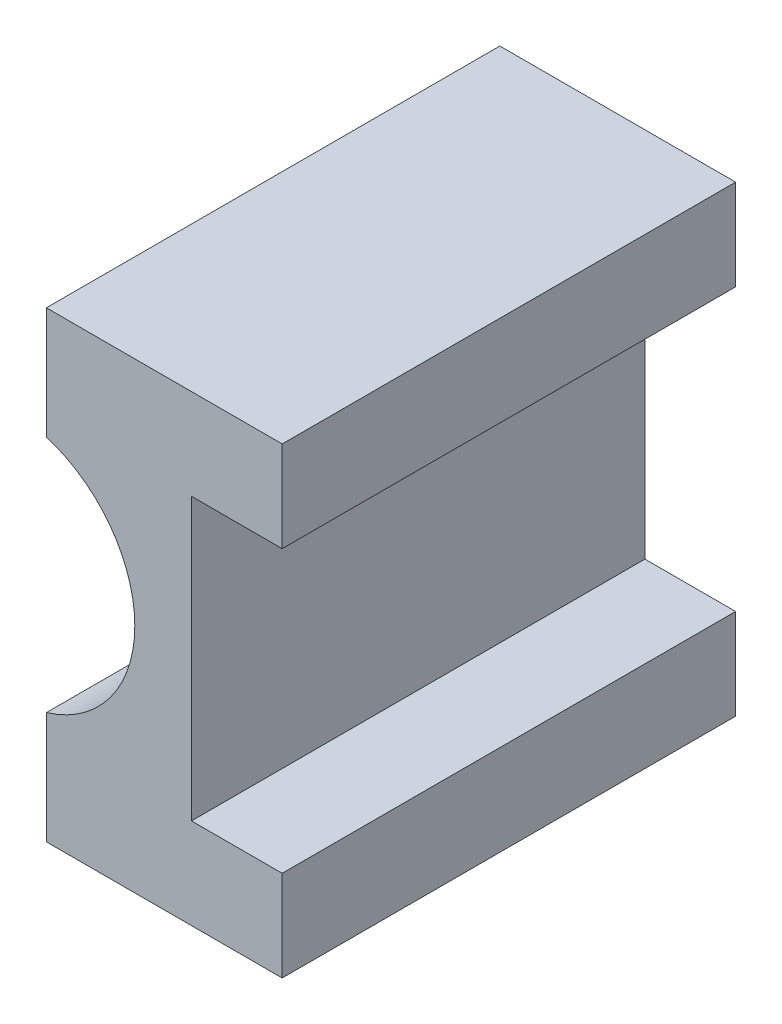
SolidWorks part; units mm, degrees
ref_plane "正面" through (0, 0, 0) normal (0, 0, 1) x (1, 0, 0)
ref_plane "平面" through (0, 0, 0) normal (0, 1, 0) x (1, 0, 0)
ref_plane "右側面" through (0, 0, 0) normal (1, 0, 0) x (0, 0, -1)
sketch "ｽｹｯﾁ1" plane through (0, 0, 0) normal (0, 0, 1) x (1, 0, 0)
  line L1 (4, -3.1) -> (4, 3.1)
  line L3 (0.8, 3) -> (0.8, 2.6311)
  line L4 (0.8, 2.6311) -> (0.8, -2.6311) construction
  line L5 (0.8, -2.6311) -> (0.8, -3)
  line L6 (0.8, -3) -> (0.8, -5.1)
  line L7 (4, 3.1) -> (6, 3.1)
  line L8 (0.8, 3) -> (0.8, 5.1)
  line L9 (0.8, 5.1) -> (6, 5.1)
  line L10 (6, 3.1) -> (6, 5.1)
  line L11 (0.8, -5.1) -> (6, -5.1)
  line L12 (6, -5.1) -> (6, -3.1)
  line L13 (6, -3.1) -> (4, -3.1)
  arc A0 (0.8, -2.6311) -> (0.8, 2.6311) centre (0, 0) ccw
  dimension "D1" = 5.5
  dimension "D2" = 4
  dimension "D3" = 3.1
  dimension "D4" = 2
  dimension "D5" = 0.8
  dimension "D6" = 2
  dimension "D7" = 2
  dimension "D8" = 3.1
  dimension "D9" = 2
extrude "ﾎﾞｽ - 押し出し1" add sketch "ｽｹｯﾁ1" along normal blind 10
